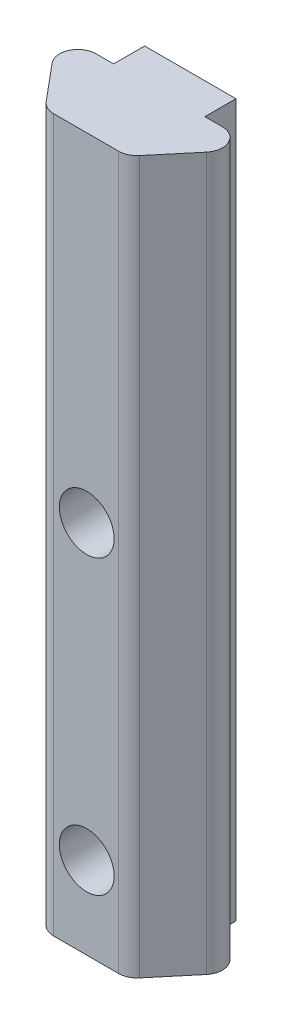
SolidWorks part; units mm, degrees
ref_plane "Front Plane" through (0, 0, 0) normal (0, 0, 1) x (1, 0, 0)
ref_plane "Top Plane" through (0, 0, 0) normal (0, 1, 0) x (1, 0, 0)
ref_plane "Right Plane" through (0, 0, 0) normal (1, 0, 0) x (0, 0, -1)
sketch "Sketch1" plane through (0, 0, 0) normal (0, 1, 0) x (1, 0, 0)
  line L0 (0.5929, 0) -> (5.1221, 0)
  line L1 (-1.5343, 5.08) -> (-0.3175, 5.08)
  line L2 (6.0957, 0.4546) -> (8.223, 2.9946)
  line L3 (-2.508, 2.9946) -> (-0.3807, 0.4546)
  line L4 (6.0325, 5.08) -> (7.2493, 5.08)
  line L6 (-0.3175, 5.08) -> (-0.3175, 7.239)
  line L7 (-0.3175, 7.239) -> (6.0325, 7.239)
  line L8 (6.0325, 5.08) -> (6.0325, 7.239)
  arc A0 (7.2493, 5.08) -> (8.223, 2.9946) centre (7.2493, 3.81) cw
  arc A1 (-1.5343, 5.08) -> (-2.508, 2.9946) centre (-1.5343, 3.81) ccw
  arc A2 (5.1221, 0) -> (6.0957, 0.4546) centre (5.1221, 1.27) ccw
  arc A3 (0.5929, 0) -> (-0.3807, 0.4546) centre (0.5929, 1.27) cw
  point P5 (2.8575, 0)
  point P8 (9.9695, 5.08)
  point P11 (-4.2545, 5.08)
  point P14 (5.715, 0)
  point P17 (0, 0)
  dimension "D5" = 1.27
  dimension "D6" = 1.27
  dimension "D1" = 5.715
  dimension "D2" = 14.224
  dimension "D3" = 4.2545
  dimension "D4" = 5.08
  dimension "D7" = 6.35
  dimension "D8" = 0.3175
  dimension "D9" = 2.159
extrude "Boss-Extrude1" add sketch "Sketch1" along normal blind 49.53 contours L6 L7 L8 L4 A0 L2 A2 L0 A3 L3 A1 L1
sketch "Sketch2" plane through (0, 0, -7.239) normal (0, 0, -1) x (-1, 0, 0)
  line L0 (0.3175, 24.765) -> (-6.0325, 24.765) construction
  line L1 (0.3175, 49.53) -> (0.3175, 0) construction
  line L2 (-6.0325, 49.53) -> (-6.0325, 0) construction
  line L4 (0.3175, 0) -> (-6.0325, 0) construction
  circle A0 centre (-2.8975, 5.715) radius 1.905
  circle A2 centre (-2.8975, 26.035) radius 1.905
  dimension "D1" = 3.81
  dimension "D3" = 20.32
  dimension "D2" = 5.715
extrude "Cut-Extrude1" cut sketch "Sketch2" against normal up to surface (7.239 mm away) up to face at (2.8575, 24.765, 0)
